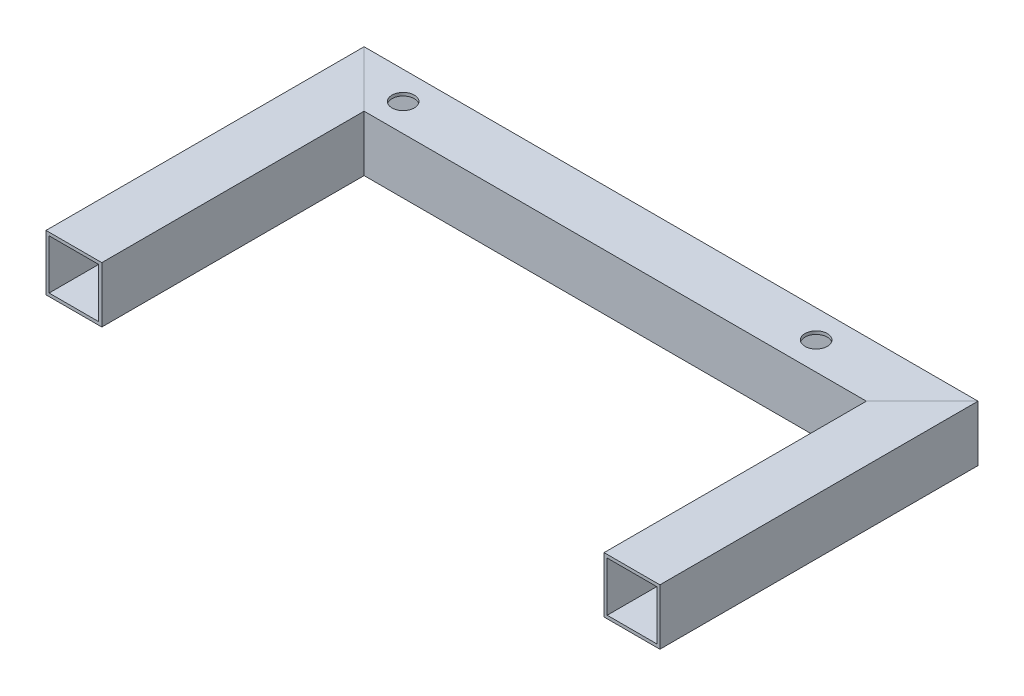
SolidWorks part; units mm, degrees
ref_plane "Front Plane" through (0, 0, 0) normal (0, 0, 1) x (1, 0, 0)
ref_plane "Top Plane" through (0, 0, 0) normal (0, 1, 0) x (1, 0, 0)
ref_plane "Right Plane" through (0, 0, 0) normal (1, 0, 0) x (0, 0, -1)
sketch "Sketch1" plane through (0, 0, 0) normal (0, 1, 0) x (1, 0, 0)
  line L0 (125, 0) -> (-125, 0)
  line L1 (-125, 0) -> (-125, -130)
  line L2 (125, 0) -> (125, -130)
  point P4 (0, 0)
  dimension "D1" = 130
  dimension "D2" = 130
  dimension "D3" = 250
ref_plane "Plane1" through (-125, 0, 130) normal (0, 0, -1) x (-1, 0, 0)
sketch "Sketch2" plane through (-125, 0, 130) normal (0, 0, -1) x (-1, 0, 0)
  line L1 (-12.5, -12.5) -> (12.5, -12.5)
  line L2 (-12.5, -12.5) -> (-12.5, 12.5)
  line L3 (-12.5, 12.5) -> (12.5, 12.5)
  line L4 (12.5, -12.5) -> (12.5, 12.5)
  line L5 (-12.5, -12.5) -> (12.5, 12.5) construction
  line L6 (-12.5, 12.5) -> (12.5, -12.5) construction
  line L7 (-11.1, -11.1) -> (11.1, -11.1)
  line L8 (-11.1, -11.1) -> (-11.1, 11.1)
  line L9 (-11.1, 11.1) -> (11.1, 11.1)
  line L10 (11.1, -11.1) -> (11.1, 11.1)
  line L11 (-11.1, -11.1) -> (11.1, 11.1) construction
  line L12 (-11.1, 11.1) -> (11.1, -11.1) construction
  point P0 (0, 0)
  point P6 (0, 0)
  dimension "D1" = 25
  dimension "D2" = 25
  dimension "D3" = 1.4
sweep "Sweep1" add profiles "Sketch2" path "Sketch1"
sketch "Sketch3" plane through (0, 12.5, 0) normal (0, 1, 0) x (1, 0, 0)
  line L0 (137.5, 12.5) -> (137.5, -130) construction
  circle A0 centre (77.5, 0) radius 5
  circle A1 centre (-107.5, 0) radius 5
  dimension "D1" = 10
  dimension "D2" = 10
  dimension "D3" = 60
  dimension "D4" = 185
extrude "Cut-Extrude1" cut sketch "Sketch3" against normal up to surface (25 mm away) up to face at (0, -12.5, 0)
